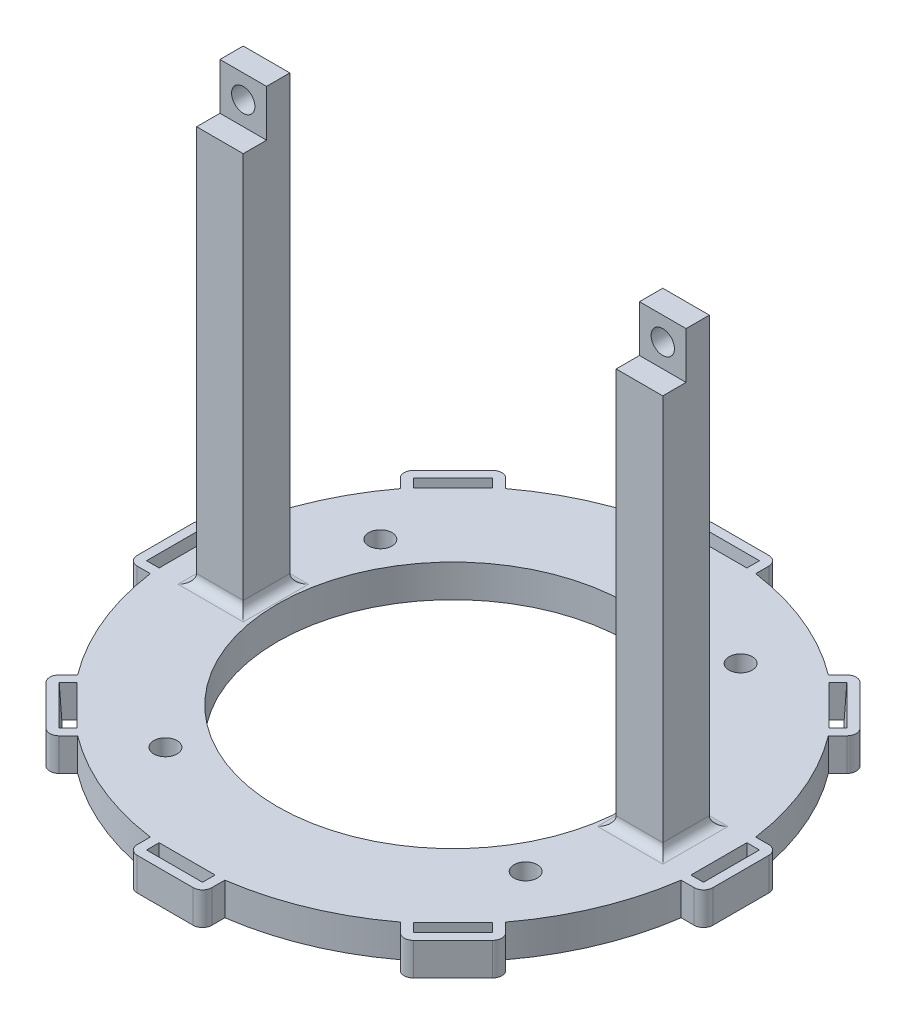
SolidWorks part; units mm, degrees
ref_plane "Front Plane" through (0, 0, 0) normal (0, 0, 1) x (1, 0, 0)
ref_plane "Top Plane" through (0, 0, 0) normal (0, 1, 0) x (1, 0, 0)
ref_plane "Right Plane" through (0, 0, 0) normal (1, 0, 0) x (0, 0, -1)
sketch "Sketch1" plane through (0, 0, 0) normal (0, 1, 0) x (1, 0, 0)
  line L0 (-8, 56.9408) -> (-8, 59.7408)
  line L1 (0, 57.5) -> (0, -57.5) construction
  line L2 (8, 56.9408) -> (8, 59.7408)
  line L3 (-6, 61.7408) -> (6, 61.7408)
  line L4 (39.4147, 47.8999) -> (47.8999, 39.4147)
  line L9 (34.6063, 45.9201) -> (36.5862, 47.8999)
  line L10 (45.9201, 34.6063) -> (47.8999, 36.5862)
  line L15 (61.7408, 6) -> (61.7408, -6)
  line L16 (56.9408, 8) -> (59.7408, 8)
  line L17 (56.9408, -8) -> (59.7408, -8)
  line L22 (47.8999, -39.4147) -> (39.4147, -47.8999)
  line L23 (45.9201, -34.6063) -> (47.8999, -36.5862)
  line L24 (34.6063, -45.9201) -> (36.5862, -47.8999)
  line L29 (6, -61.7408) -> (-6, -61.7408)
  line L30 (8, -56.9408) -> (8, -59.7408)
  line L31 (-8, -56.9408) -> (-8, -59.7408)
  line L36 (-39.4147, -47.8999) -> (-47.8999, -39.4147)
  line L37 (-34.6063, -45.9201) -> (-36.5862, -47.8999)
  line L38 (-45.9201, -34.6063) -> (-47.8999, -36.5862)
  line L43 (-61.7408, -6) -> (-61.7408, 6)
  line L44 (-56.9408, -8) -> (-59.7408, -8)
  line L45 (-56.9408, 8) -> (-59.7408, 8)
  line L50 (-47.8999, 39.4147) -> (-39.4147, 47.8999)
  line L51 (-45.9201, 34.6063) -> (-47.8999, 36.5862)
  line L52 (-34.6063, 45.9201) -> (-36.5862, 47.8999)
  arc A0 (-8, 56.9408) -> (-34.6063, 45.9201) centre (0, 0) ccw
  arc A1 (6, 61.7408) -> (8, 59.7408) centre (6, 59.7408) cw
  arc A2 (-6, 61.7408) -> (-8, 59.7408) centre (-6, 59.7408) ccw
  arc A3 (39.4147, 47.8999) -> (36.5862, 47.8999) centre (38.0005, 46.4857) ccw
  arc A4 (47.8999, 39.4147) -> (47.8999, 36.5862) centre (46.4857, 38.0005) cw
  arc A5 (61.7408, 6) -> (59.7408, 8) centre (59.7408, 6) ccw
  arc A6 (61.7408, -6) -> (59.7408, -8) centre (59.7408, -6) cw
  arc A7 (47.8999, -39.4147) -> (47.8999, -36.5862) centre (46.4857, -38.0005) ccw
  arc A8 (39.4147, -47.8999) -> (36.5862, -47.8999) centre (38.0005, -46.4857) cw
  arc A9 (6, -61.7408) -> (8, -59.7408) centre (6, -59.7408) ccw
  arc A10 (-6, -61.7408) -> (-8, -59.7408) centre (-6, -59.7408) cw
  arc A11 (-39.4147, -47.8999) -> (-36.5862, -47.8999) centre (-38.0005, -46.4857) ccw
  arc A12 (-47.8999, -39.4147) -> (-47.8999, -36.5862) centre (-46.4857, -38.0005) cw
  arc A13 (-61.7408, -6) -> (-59.7408, -8) centre (-59.7408, -6) ccw
  arc A14 (-61.7408, 6) -> (-59.7408, 8) centre (-59.7408, 6) cw
  arc A15 (-47.8999, 39.4147) -> (-47.8999, 36.5862) centre (-46.4857, 38.0005) ccw
  arc A16 (-39.4147, 47.8999) -> (-36.5862, 47.8999) centre (-38.0005, 46.4857) cw
  arc A17 (-45.9201, 34.6063) -> (-56.9408, 8) centre (0, 0) ccw
  arc A18 (-56.9408, -8) -> (-45.9201, -34.6063) centre (0, 0) ccw
  arc A19 (34.6063, 45.9201) -> (8, 56.9408) centre (0, 0) ccw
  arc A20 (-34.6063, -45.9201) -> (-8, -56.9408) centre (0, 0) ccw
  arc A21 (8, -56.9408) -> (34.6063, -45.9201) centre (0, 0) ccw
  arc A22 (45.9201, -34.6063) -> (56.9408, -8) centre (0, 0) ccw
  arc A23 (56.9408, 8) -> (45.9201, 34.6063) centre (0, 0) ccw
  point P11 (8, 61.7408)
  point P14 (-8, 61.7408)
  point P17 (-8, 58.3408)
  point P98 (0, 0)
  dimension "D1" = 115
  dimension "D2" = 2
  dimension "D3" = 16
  dimension "D4" = 2.8
  dimension "D7" = 8
extrude "Boss-Extrude1" add sketch "Sketch1" along normal blind 7
sketch "Sketch2" plane through (0, 7, 0) normal (0, 1, 0) x (1, 0, 0)
  line L0 (-57.5, 0) -> (57.5, 0) construction
  line L1 (0, 57.5) -> (0, -57.5) construction
  line L2 (40, 5) -> (50, 5)
  line L3 (40, 5) -> (40, -5)
  line L4 (40, -5) -> (50, -5)
  line L5 (50, 5) -> (50, -5)
  line L6 (40, 5) -> (50, -5) construction
  line L7 (40, -5) -> (50, 5) construction
  line L8 (-40, -5) -> (-50, -5)
  line L9 (-50, 5) -> (-50, -5)
  line L10 (-40, 5) -> (-50, 5)
  line L11 (-40, 5) -> (-40, -5)
  circle A0 centre (0, 0) radius 57.5 construction
  point P5 (45, 0)
  point P16 (-45, 0)
  point P22 (-45, -5)
  dimension "D1" = 10
  dimension "D2" = 10
  dimension "D3" = 80
extrude "Boss-Extrude2" add sketch "Sketch2" along normal blind 95
sketch "Sketch3" plane through (0, 7, 0) normal (0, 1, 0) x (1, 0, 0)
  circle A0 centre (0, 0) radius 37.6637
extrude "Cut-Extrude1" cut sketch "Sketch3" against normal through all
sketch "Sketch5" plane through (0, 7, 0) normal (0, 1, 0) x (1, 0, 0)
  line L1 (-6, 59.7408) -> (6, 59.7408)
  line L2 (-6, 59.7408) -> (-6, 57.0408)
  line L3 (-6, 57.0408) -> (6, 57.0408)
  line L4 (6, 59.7408) -> (6, 57.0408)
  line L24 (8, 56.9408) -> (8, 59.7408)
  line L25 (6, 61.7408) -> (-6, 61.7408)
  line L26 (-8, 59.7408) -> (-8, 56.9408)
  line L27 (-34.6063, 45.9201) -> (-36.5862, 47.8999)
  line L28 (-39.4147, 47.8999) -> (-47.8999, 39.4147)
  line L29 (-47.8999, 36.5862) -> (-45.9201, 34.6063)
  line L30 (-56.9408, 8) -> (-59.7408, 8)
  line L31 (-61.7408, 6) -> (-61.7408, -6)
  line L32 (-59.7408, -8) -> (-56.9408, -8)
  line L33 (-45.9201, -34.6063) -> (-47.8999, -36.5862)
  line L34 (-47.8999, -39.4147) -> (-39.4147, -47.8999)
  line L35 (-36.5862, -47.8999) -> (-34.6063, -45.9201)
  line L36 (-8, -56.9408) -> (-8, -59.7408)
  line L37 (-6, -61.7408) -> (6, -61.7408)
  line L38 (8, -59.7408) -> (8, -56.9408)
  line L39 (34.6063, -45.9201) -> (36.5862, -47.8999)
  line L40 (39.4147, -47.8999) -> (47.8999, -39.4147)
  line L41 (47.8999, -36.5862) -> (45.9201, -34.6063)
  line L42 (56.9408, -8) -> (59.7408, -8)
  line L43 (61.7408, -6) -> (61.7408, 6)
  line L44 (59.7408, 8) -> (56.9408, 8)
  line L45 (45.9201, 34.6063) -> (47.8999, 36.5862)
  line L46 (47.8999, 39.4147) -> (39.4147, 47.8999)
  line L47 (36.5862, 47.8999) -> (34.6063, 45.9201)
  line L48 (8, 56.9408) -> (8, 59.7408)
  line L49 (6, 61.7408) -> (-6, 61.7408)
  line L50 (-8, 59.7408) -> (-8, 56.9408)
  line L51 (-34.6063, 45.9201) -> (-36.5862, 47.8999)
  line L52 (-39.4147, 47.8999) -> (-47.8999, 39.4147)
  line L53 (-47.8999, 36.5862) -> (-45.9201, 34.6063)
  line L54 (-56.9408, 8) -> (-59.7408, 8)
  line L55 (-61.7408, 6) -> (-61.7408, -6)
  line L56 (-59.7408, -8) -> (-56.9408, -8)
  line L57 (-45.9201, -34.6063) -> (-47.8999, -36.5862)
  line L58 (-47.8999, -39.4147) -> (-39.4147, -47.8999)
  line L59 (-36.5862, -47.8999) -> (-34.6063, -45.9201)
  line L60 (-8, -56.9408) -> (-8, -59.7408)
  line L61 (-6, -61.7408) -> (6, -61.7408)
  line L62 (8, -59.7408) -> (8, -56.9408)
  line L63 (34.6063, -45.9201) -> (36.5862, -47.8999)
  line L64 (39.4147, -47.8999) -> (47.8999, -39.4147)
  line L65 (47.8999, -36.5862) -> (45.9201, -34.6063)
  line L66 (56.9408, -8) -> (59.7408, -8)
  line L67 (61.7408, -6) -> (61.7408, 6)
  line L68 (59.7408, 8) -> (56.9408, 8)
  line L69 (45.9201, 34.6063) -> (47.8999, 36.5862)
  line L70 (47.8999, 39.4147) -> (39.4147, 47.8999)
  line L71 (36.5862, 47.8999) -> (34.6063, 45.9201)
  arc A24 (34.6063, 45.9201) -> (8, 56.9408) centre (0, 0) ccw
  arc A25 (8, 59.7408) -> (6, 61.7408) centre (6, 59.7408) ccw
  arc A26 (-6, 61.7408) -> (-8, 59.7408) centre (-6, 59.7408) ccw
  arc A27 (-8, 56.9408) -> (-34.6063, 45.9201) centre (0, 0) ccw
  arc A28 (-36.5862, 47.8999) -> (-39.4147, 47.8999) centre (-38.0005, 46.4857) ccw
  arc A29 (-47.8999, 39.4147) -> (-47.8999, 36.5862) centre (-46.4857, 38.0005) ccw
  arc A30 (-45.9201, 34.6063) -> (-56.9408, 8) centre (0, 0) ccw
  arc A31 (-59.7408, 8) -> (-61.7408, 6) centre (-59.7408, 6) ccw
  arc A32 (-61.7408, -6) -> (-59.7408, -8) centre (-59.7408, -6) ccw
  arc A33 (-56.9408, -8) -> (-45.9201, -34.6063) centre (0, 0) ccw
  arc A34 (-47.8999, -36.5862) -> (-47.8999, -39.4147) centre (-46.4857, -38.0005) ccw
  arc A35 (-39.4147, -47.8999) -> (-36.5862, -47.8999) centre (-38.0005, -46.4857) ccw
  arc A36 (-34.6063, -45.9201) -> (-8, -56.9408) centre (0, 0) ccw
  arc A37 (-8, -59.7408) -> (-6, -61.7408) centre (-6, -59.7408) ccw
  arc A38 (6, -61.7408) -> (8, -59.7408) centre (6, -59.7408) ccw
  arc A39 (8, -56.9408) -> (34.6063, -45.9201) centre (0, 0) ccw
  arc A40 (36.5862, -47.8999) -> (39.4147, -47.8999) centre (38.0005, -46.4857) ccw
  arc A41 (47.8999, -39.4147) -> (47.8999, -36.5862) centre (46.4857, -38.0005) ccw
  arc A42 (45.9201, -34.6063) -> (56.9408, -8) centre (0, 0) ccw
  arc A43 (59.7408, -8) -> (61.7408, -6) centre (59.7408, -6) ccw
  arc A44 (61.7408, 6) -> (59.7408, 8) centre (59.7408, 6) ccw
  arc A45 (56.9408, 8) -> (45.9201, 34.6063) centre (0, 0) ccw
  arc A46 (47.8999, 36.5862) -> (47.8999, 39.4147) centre (46.4857, 38.0005) ccw
  arc A47 (39.4147, 47.8999) -> (36.5862, 47.8999) centre (38.0005, 46.4857) ccw
  arc A48 (34.6063, 45.9201) -> (8, 56.9408) centre (0, 0) ccw
  arc A49 (8, 59.7408) -> (6, 61.7408) centre (6, 59.7408) ccw
  arc A50 (-6, 61.7408) -> (-8, 59.7408) centre (-6, 59.7408) ccw
  arc A51 (-8, 56.9408) -> (-34.6063, 45.9201) centre (0, 0) ccw
  arc A52 (-36.5862, 47.8999) -> (-39.4147, 47.8999) centre (-38.0005, 46.4857) ccw
  arc A53 (-47.8999, 39.4147) -> (-47.8999, 36.5862) centre (-46.4857, 38.0005) ccw
  arc A54 (-45.9201, 34.6063) -> (-56.9408, 8) centre (0, 0) ccw
  arc A55 (-59.7408, 8) -> (-61.7408, 6) centre (-59.7408, 6) ccw
  arc A56 (-61.7408, -6) -> (-59.7408, -8) centre (-59.7408, -6) ccw
  arc A57 (-56.9408, -8) -> (-45.9201, -34.6063) centre (0, 0) ccw
  arc A58 (-47.8999, -36.5862) -> (-47.8999, -39.4147) centre (-46.4857, -38.0005) ccw
  arc A59 (-39.4147, -47.8999) -> (-36.5862, -47.8999) centre (-38.0005, -46.4857) ccw
  arc A60 (-34.6063, -45.9201) -> (-8, -56.9408) centre (0, 0) ccw
  arc A61 (-8, -59.7408) -> (-6, -61.7408) centre (-6, -59.7408) ccw
  arc A62 (6, -61.7408) -> (8, -59.7408) centre (6, -59.7408) ccw
  arc A63 (8, -56.9408) -> (34.6063, -45.9201) centre (0, 0) ccw
  arc A64 (36.5862, -47.8999) -> (39.4147, -47.8999) centre (38.0005, -46.4857) ccw
  arc A65 (47.8999, -39.4147) -> (47.8999, -36.5862) centre (46.4857, -38.0005) ccw
  arc A66 (45.9201, -34.6063) -> (56.9408, -8) centre (0, 0) ccw
  arc A67 (59.7408, -8) -> (61.7408, -6) centre (59.7408, -6) ccw
  arc A68 (61.7408, 6) -> (59.7408, 8) centre (59.7408, 6) ccw
  arc A69 (56.9408, 8) -> (45.9201, 34.6063) centre (0, 0) ccw
  arc A70 (47.8999, 36.5862) -> (47.8999, 39.4147) centre (46.4857, 38.0005) ccw
  arc A71 (39.4147, 47.8999) -> (36.5862, 47.8999) centre (38.0005, 46.4857) ccw
  dimension "D2" = 12
  dimension "D3" = 2.7
  dimension "D1" = 0
sketch "Sketch7" plane through (0, 0, 0) normal (0, -1, 0) x (1, 0, 0)
  line L0 (6, -59.7408) -> (6, -57.0408) construction
  line L1 (-6, -57.0408) -> (6, -57.0408)
  line L2 (-6, -57.0408) -> (-6, -59.3408)
  line L3 (-6, -59.3408) -> (6, -59.3408)
  line L4 (6, -57.0408) -> (6, -59.3408)
  dimension "D1" = 2.3
loft "Cut-Loft1" cut profiles "Sketch7" section "Sketch7" section "Sketch5"
sketch "Sketch9" plane through (0, 0, 0) normal (1, 0, 0) x (0, 0, -1)
  line L0 (0, 102) -> (0, 0) construction
  line L1 (-5, 102) -> (5, 102) construction
pattern_circular "CirPattern1" count 8 over 360 about axis through (0, 0, 0) along (0, 1, 0) of "Cut-Loft1"
sketch "Sketch13" plane through (0, 0, -5) normal (0, 0, -1) x (-1, 0, 0)
  line L0 (-45, 102) -> (-45, 7) construction
  line L1 (-50, 102) -> (-40, 102) construction
  line L2 (-50, 7) -> (-40, 7) construction
sketch "Sketch14" plane through (0, 0, 0) normal (0, -1, 0) x (1, 0, 0)
  line L0 (0, 0) -> (38.6439, 23.0575) construction
  line L1 (-59.3408, 6) -> (-59.3408, -6) construction
  line L2 (-57.0408, 6) -> (-59.3408, 6) construction
  circle A1 centre (38.6439, 23.0575) radius 2.5
  dimension "D1" = 97.9847
  dimension "D2" = 5
  dimension "D3" = 45
extrude "Cut-Extrude2" cut sketch "Sketch14" against normal up to surface (7 mm away) up to face at (39.6445, 7, -43.8871)
pattern_circular "CirPattern2" count 4 every 90 about axis through (0, 0, 0) along (0, 1, 0) of "Cut-Extrude2"
sketch "Sketch15" plane through (40, 0, 0) normal (-1, 0, 0) x (0, 0, 1)
  line L6 (-5, 102) -> (5, 102) construction
  line L7 (0, 102) -> (5, 102)
  line L8 (0, 102) -> (0, 92)
  line L9 (0, 92) -> (5, 92)
  line L10 (5, 102) -> (5, 92)
  line L11 (5, 102) -> (5, 7) construction
  dimension "D1" = 10
extrude "Cut-Extrude3" cut sketch "Sketch15" against normal through all both and the other way through all
sketch "Sketch16" plane through (0, 0, 0) normal (0, 0, 1) x (1, 0, 0)
  line L0 (45, 102) -> (45, 92) construction
  line L1 (50, 102) -> (40, 102) construction
  line L2 (50, 92) -> (40, 92) construction
  circle A0 centre (45, 97) radius 2.5
  dimension "D1" = 5
extrude "Cut-Extrude4" cut sketch "Sketch16" against normal up to next
mirror "Mirror1" about plane through (0, 0, 0) normal (1, 0, 0) of "Cut-Extrude4"
sketch "Sketch17" plane through (0, 0, 0) normal (0, 0, 1) x (1, 0, 0)
  line L0 (-50, 102) -> (50, 102) construction
fillet "Fillet1" radius 2 8 edges at (40, 7, 0) (45, 7, -5) (50, 7, 0) (45, 7, 5) (-40, 7, 0) (-45, 7, -5) (-50, 7, 0) (-45, 7, 5)
equation "\"85.00.00mm\"=8500"
